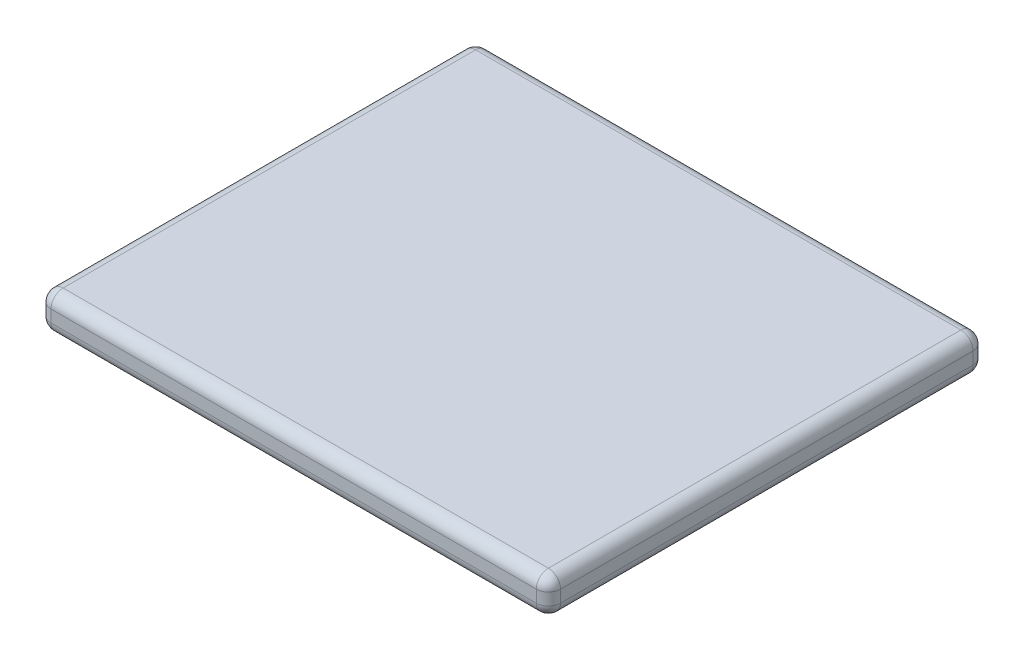
SolidWorks part; units mm, degrees
ref_plane "Front Plane" through (0, 0, 0) normal (0, 0, 1) x (1, 0, 0)
ref_plane "Top Plane" through (0, 0, 0) normal (0, 1, 0) x (1, 0, 0)
ref_plane "Right Plane" through (0, 0, 0) normal (1, 0, 0) x (0, 0, -1)
sketch "Sketch1" plane through (0, 0, 0) normal (0, 1, 0) x (1, 0, 0)
  line L0 (0, 36) -> (0, -36) construction
  line L1 (-40, 36) -> (40, 36)
  line L2 (-42, 34) -> (-42, -34)
  line L3 (-40, -36) -> (40, -36)
  line L4 (42, 34) -> (42, -34)
  arc A0 (-42, -34) -> (-40, -36) centre (-40, -34) ccw
  arc A1 (40, -36) -> (42, -34) centre (40, -34) ccw
  arc A2 (40, 36) -> (42, 34) centre (40, 34) cw
  arc A3 (-40, 36) -> (-42, 34) centre (-40, 34) ccw
  point P6 (0, 0)
  point P10 (-42, -36)
  point P15 (42, 36)
  point P18 (-42, 36)
  dimension "D3" = 2
  dimension "D1" = 84
  dimension "D2" = 72
extrude "Boss-Extrude1" add sketch "Sketch1" along normal blind 6
fillet "Fillet1" radius 2 16 edges at (41.4142, 0, 35.4142) (41.4142, 0, -35.4142) (-41.4142, 0, -35.4142) (-41.4142, 0, 35.4142) (-42, 0, 0) (0, 0, -36) (42, 0, 0) (0, 0, 36) (-42, 6, 0) (-41.4142, 6, -35.4142) (0, 6, -36) (41.4142, 6, -35.4142) (42, 6, 0) (41.4142, 6, 35.4142) (0, 6, 36) (-41.4142, 6, 35.4142)
